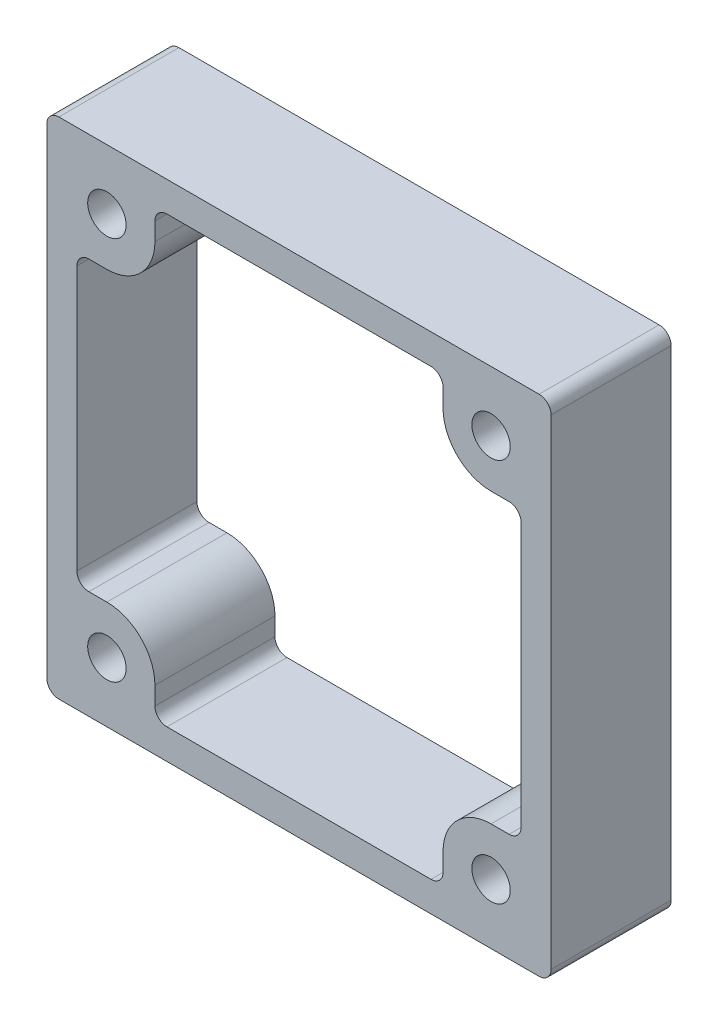
SolidWorks part; units mm, degrees
ref_plane "Front Plane" through (0, 0, 0) normal (0, 0, 1) x (1, 0, 0)
ref_plane "Top Plane" through (0, 0, 0) normal (0, 1, 0) x (1, 0, 0)
ref_plane "Right Plane" through (0, 0, 0) normal (1, 0, 0) x (0, 0, -1)
sketch "Sketch1" plane through (0, 0, 0) normal (0, 0, 1) x (1, 0, 0)
  line L4 (0, -1) -> (40, -1)
  line L5 (41, 0) -> (41, 40)
  line L6 (40, 41) -> (0, 41)
  line L7 (-1, 40) -> (-1, 0)
  line L11 (36, 8) -> (37.5, 8)
  line L13 (36, 32) -> (37.5, 32)
  line L14 (1.5, 9) -> (1.5, 31)
  line L15 (9, 38.5) -> (31, 38.5)
  line L16 (38.5, 31) -> (38.5, 9)
  line L17 (31, 1.5) -> (9, 1.5)
  line L20 (2.5, 8) -> (4, 8)
  line L21 (8, 4) -> (8, 2.5)
  line L22 (32, 4) -> (32, 2.5)
  line L23 (32, 36) -> (32, 37.5)
  line L24 (8, 36) -> (8, 37.5)
  line L25 (4, 32) -> (2.5, 32)
  arc A0 (0, -1) -> (-1, 0) centre (0, 0) cw
  arc A1 (40, -1) -> (41, 0) centre (40, 0) ccw
  arc A2 (41, 40) -> (40, 41) centre (40, 40) ccw
  arc A3 (0, 41) -> (-1, 40) centre (0, 40) ccw
  circle A4 centre (4, 36) radius 1.6
  circle A5 centre (36, 36) radius 1.6
  circle A6 centre (36, 4) radius 1.6
  circle A7 centre (4, 4) radius 1.6
  arc A8 (38.5, 31) -> (37.5, 32) centre (37.5, 31) ccw
  arc A9 (31, 38.5) -> (32, 37.5) centre (31, 37.5) cw
  arc A10 (8, 37.5) -> (9, 38.5) centre (9, 37.5) cw
  arc A11 (2.5, 32) -> (1.5, 31) centre (2.5, 31) ccw
  arc A12 (1.5, 9) -> (2.5, 8) centre (2.5, 9) ccw
  arc A13 (4, 32) -> (8, 36) centre (4, 36) ccw
  arc A14 (32, 36) -> (36, 32) centre (36, 36) ccw
  arc A15 (36, 8) -> (32, 4) centre (36, 4) ccw
  arc A16 (8, 4) -> (4, 8) centre (4, 4) ccw
  arc A17 (38.5, 9) -> (37.5, 8) centre (37.5, 9) cw
  arc A18 (31, 1.5) -> (32, 2.5) centre (31, 2.5) ccw
  arc A19 (9, 1.5) -> (8, 2.5) centre (9, 2.5) cw
  point P28 (0, 0)
  dimension "D1" = 1
  dimension "D2" = 1
extrude "Boss-Extrude1" add sketch "Sketch1" along normal blind 10
